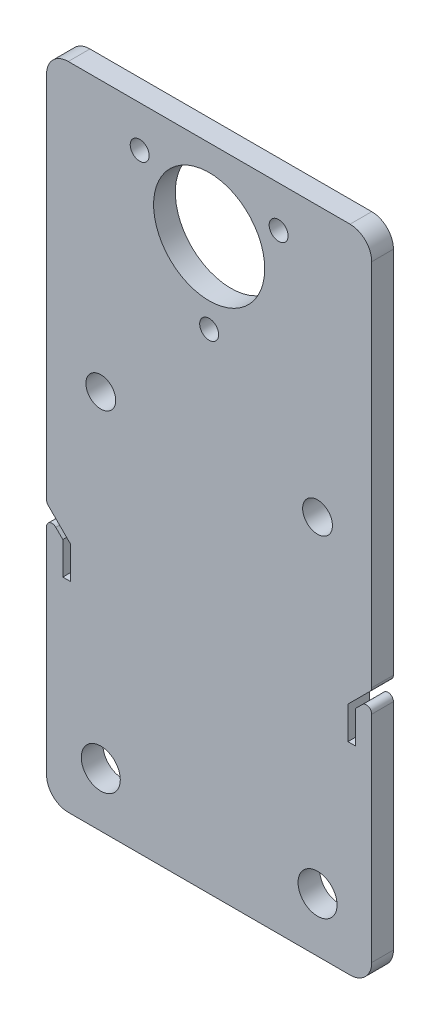
SolidWorks part; units mm, degrees
ref_plane "Płaszczyzna przednia" through (0, 0, 0) normal (0, 0, 1) x (1, 0, 0)
ref_plane "Płaszczyzna górna" through (0, 0, 0) normal (0, 1, 0) x (1, 0, 0)
ref_plane "Płaszczyzna prawa" through (0, 0, 0) normal (1, 0, 0) x (0, 0, -1)
sketch "Szkic1" plane through (0, 0, 0) normal (0, 0, 1) x (1, 0, 0)
  line L0 (19.1159, 65.7063) -> (19.1159, 95.5063) construction
  line L1 (-10.8841, -24.4937) -> (49.1159, -24.4937)
  line L2 (-10.8841, -24.4937) -> (-10.8841, 95.5063)
  line L3 (-10.8841, 95.5063) -> (49.1159, 95.5063)
  line L4 (49.1159, -24.4937) -> (49.1159, 95.5063)
  circle A0 centre (-0.8841, 45.7063) radius 2.75
  circle A1 centre (-0.8841, -14.4937) radius 3.6
  circle A2 centre (39.1159, -14.4937) radius 3.6
  circle A3 centre (39.1159, 45.7063) radius 2.75
  circle A4 centre (19.1159, 80.5063) radius 10.25
  circle A5 centre (6.2988, 87.9063) radius 1.75
  circle A6 centre (31.9331, 87.9063) radius 1.75
  circle A7 centre (19.1159, 65.7063) radius 1.75
  dimension "D11" = 7.2
  dimension "D12" = 5.5
  dimension "D13" = 5.5
  dimension "D14" = 7.2
  dimension "D15" = 3.5
  dimension "D16" = 3.5
  dimension "D17" = 20.5
  dimension "3,5" = 3.5
  dimension "D18" = 14.8
  dimension "D19" = 14.8
  dimension "D20" = 14.8
  dimension "D3" = 60.2
  dimension "D4" = 60.2
  dimension "D5" = 10
  dimension "D6" = 10
  dimension "D7" = 10
  dimension "D8" = 10
  dimension "D9" = 60
  dimension "D10" = 120
  dimension "D21" = 10
  dimension "D22" = 10
  dimension "D23" = 30
  dimension "D24" = 15
extrude "Dodanie-wyciągnięcie1" add sketch "Szkic1" along normal blind 4
fillet "Zaokrąglenie1" radius 4 4 edges at (49.1159, 95.5063, 2) (49.1159, -24.4937, 2) (-10.8841, -24.4937, 2) (-10.8841, 95.5063, 2)
sketch "Szkic2" plane through (0, 0, 4) normal (0, 0, 1) x (1, 0, 0)
  line L0 (-10.8841, 91.5063) -> (-10.8841, -20.4937) construction
  line L2 (-7.8841, 18.6063) -> (-7.8841, 12.6063)
  line L3 (-7.8841, 12.6063) -> (-6.4841, 12.6063)
  line L4 (-6.4841, 18.6063) -> (-6.4841, 12.6063)
  line L6 (44.7159, 18.6063) -> (44.7159, 12.6063)
  line L7 (44.7159, 12.6063) -> (46.1159, 12.6063)
  line L8 (46.1159, 18.6063) -> (46.1159, 12.6063)
  line L9 (49.1159, -20.4937) -> (49.1159, 91.5063) construction
  line L10 (-7.8841, 18.6063) -> (-10.8841, 21.6063)
  line L11 (-10.8841, 21.6063) -> (-10.8841, 23.0063)
  line L12 (-10.8841, 23.0063) -> (-6.4841, 18.6063)
  line L13 (44.7159, 18.6063) -> (49.1159, 23.0063)
  line L14 (49.1159, 23.0063) -> (49.1159, 21.6063)
  line L15 (49.1159, 21.6063) -> (46.1159, 18.6063)
  line L16 (-7.8841, 18.6063) -> (-6.4841, 18.6063)
  line L17 (44.7159, 18.6063) -> (46.1159, 18.6063)
  circle A0 centre (-0.8841, -14.4937) radius 3.6 construction
  circle A1 centre (-0.8841, 45.7063) radius 2.75 construction
  circle A2 centre (39.1159, 45.7063) radius 2.75 construction
  circle A3 centre (39.1159, -14.4937) radius 3.6 construction
  point P12 (-6.4841, 15.6063)
  point P17 (44.7159, 15.6063)
  line M5 (49.1159, -20.4937) -> (49.1159, 91.5063)
  line M9 (-10.8841, 91.5063) -> (-10.8841, -20.4937)
  dimension "D7" = 30.1
  dimension "D8" = 30.1
  dimension "D9" = 30.1
  dimension "D1" = 6
  dimension "D2" = 1.4
  dimension "D3" = 1.4
  dimension "D4" = 3
  dimension "D5" = 6
  dimension "D6" = 3
  dimension "D10" = 45
  dimension "D11" = 45
  dimension "D12" = 30.1
extrude "Wytnij-wyciągnięcie1" cut sketch "Szkic2" against normal blind 10 contours L16 L2 L3 L4 | L10 L16 L12 M9 | L13 L17 L15 M5 | L17 L6 L7 L8
fillet "Zaokrąglenie2" radius 1 2 edges at (49.1159, 21.6063, 2) (49.1159, 23.0063, 2)
fillet "Zaokrąglenie3" radius 1 2 edges at (-10.8841, 23.0063, 2) (-10.8841, 21.6063, 2)
